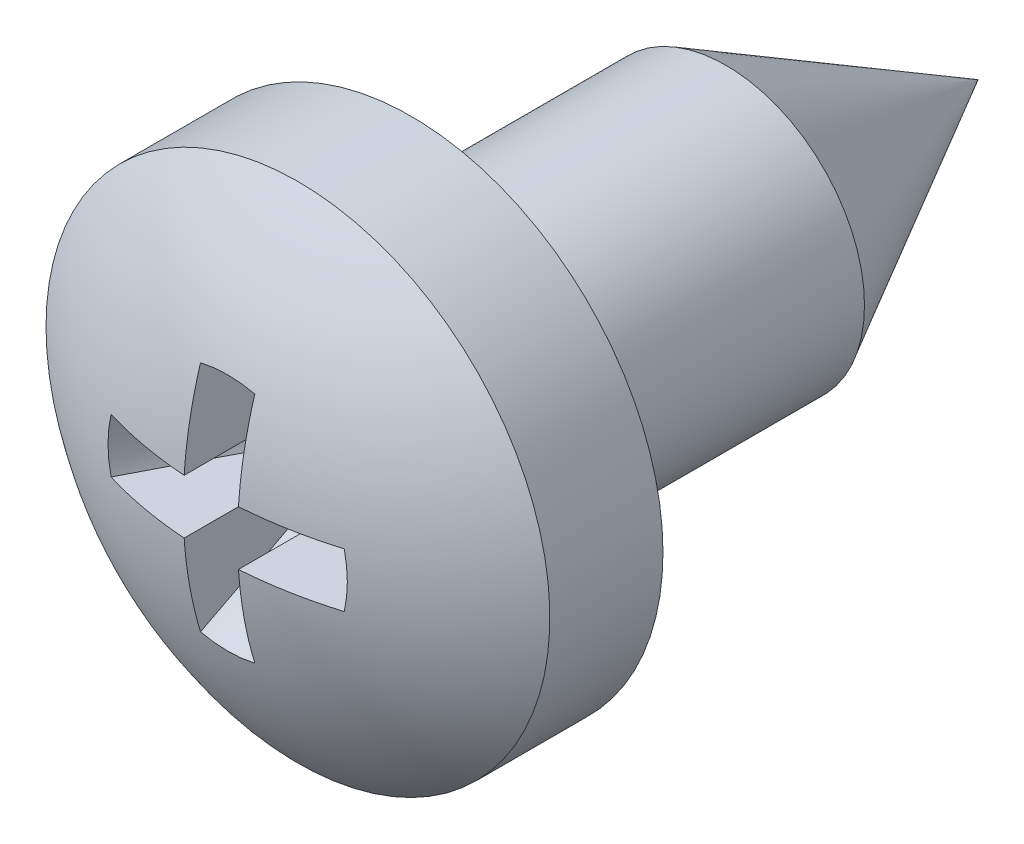
SolidWorks part; units mm, degrees
material "Alloy Steel"
ref_plane "Спереди" through (0, 0, 0) normal (0, 0, 1) x (1, 0, 0)
ref_plane "Сверху" through (0, 0, 0) normal (0, 1, 0) x (1, 0, 0)
ref_plane "Справа" through (0, 0, 0) normal (1, 0, 0) x (0, 0, -1)
sketch "Sketch1" plane through (0, 0, 0) normal (1, 0, 0) x (0, 0, -1)
  line L0 (104.6162, 0) -> (-104.6162, 0) construction
  line L1 (0, -65.8131) -> (0, 65.8131) construction
  line L3 (0.702, 2) -> (1.6, 2)
  line L4 (1.6, 2) -> (1.6, 1.1)
  line L5 (1.6, 1.1) -> (6.1, 1.1)
  line L6 (6.1, 1.1) -> (6.1, 0)
  line L7 (6.1, 0) -> (0, 0)
  arc A0 (0.702, 2) -> (0, 0) centre (3.2, 0) ccw
  point P4 (0, 0)
  point P8 (0, 0)
  dimension "D1" = 3.2
  dimension "D4" = 4
  dimension "D5" = 2.2
  dimension "D2" = 1.6
  dimension "D3" = 4.5
revolve "BaseBody" add sketch "Sketch1" angle 360 about L0
cosmetic thread "Cosmetic Thread1" parameters "D1"=3.7, "D2"=1.63
cosmetic thread "Cosmetic Thread2" [suppressed] parameters "D1"=3.7, "D2"=1.63
cosmetic thread "Cosmetic Thread3" [suppressed] parameters "D1"=3.7, "D2"=1.63
sketch "Sketch2" plane through (0, 0, 0) normal (0, 0, 1) x (1, 0, 0)
  line L0 (2.967, 0) -> (-2.967, 0) construction
  line L1 (0, -2.1958) -> (0, 2.1958) construction
  line L2 (-0.2157, 0.9252) -> (-0.2157, 0)
  line L3 (-0.2157, 0) -> (0.2157, 0)
  line L4 (0.2157, 0) -> (0.2157, 0.9252)
  line L5 (0.2157, 0) -> (-0.2157, 0.4313) construction
  arc A0 (0.2157, 0.9252) -> (-0.2157, 0.9252) centre (0, 0) ccw
  point P4 (0, 0)
  point P8 (0, 0)
  dimension "m" = 1.9
  dimension "D2" = 45
  dimension "D3" = 0.61
extrude "Slot" cut sketch "Sketch2" against normal blind 1.9
pattern_circular "CirPattern1" count 4 over 360 about axis through (0, 0, 0) along (0, 0, 1) of "Slot"
sketch "Sketch3" [suppressed] plane through (0, 0, 0) normal (0, 0, 1) x (1, 0, 0)
  line L0 (2.5828, 0) -> (-2.5828, 0) construction
  line L1 (0, -2.1055) -> (0, 2.1055) construction
  line L2 (0, 0) -> (-1.0643, 1.0643) construction
  line L3 (-0.7071, 0.7071) -> (-0.4001, 0.2687)
  line L4 (-0.4001, 0.2687) -> (-0.2687, 0.2687)
  line L5 (-0.2687, 0.2687) -> (-0.2687, 0.4001)
  line L6 (-0.2687, 0.4001) -> (-0.7071, 0.7071)
  line L7 (0.2687, 0) -> (0.2687, 0.9632) construction
  line L8 (-0.2687, 0.9632) -> (-0.2687, 0) construction
  line L9 (0.2687, 0) -> (-0.2687, 0.5374) construction
  circle A0 centre (0, 0) radius 1 construction
  point P4 (0, 0)
  point P8 (0, 0)
  dimension "D4" = 1.9
  dimension "D1" = 45
  dimension "D2" = 10
  dimension "D3" = 10
  dimension "u" = 0.95
  dimension "D5" = 0.61
  dimension "D6" = 45
extrude "Slot2" [suppressed] cut sketch "Sketch3" against normal blind 1.9
pattern_circular "CirPattern2" [suppressed] count 4 over 360
sketch "Sketch4" plane through (0, 0, 0) normal (1, 0, 0) x (0, 0, -1)
  line L0 (5.0682, 0) -> (-5.0682, 0) construction
  line L1 (0.6251, 1.9) -> (1.6, 1.9)
  line L2 (0, -2.7234) -> (0, 2.7234) construction
  line L5 (1.6, 1.9) -> (1.6, 1.1)
  line L6 (1.6, 1.1) -> (1.91, 1.1)
  line L7 (1.91, 1.1) -> (1.91, 0)
  line L8 (1.91, 0) -> (1.4527, 0)
  line L10 (1.4527, 0) -> (1.2374, 0.405)
  line L11 (1.2374, 0.405) -> (0.1443, 0.95)
  arc A0 (0.6251, 1.9) -> (0.1443, 0.95) centre (3.2, 0) ccw
  point P3 (0, 0)
  point P7 (0, 0)
  dimension "D4" = 1.9
  dimension "D3" = 3.2
  dimension "D1" = 28
  dimension "D2" = 26.5
  dimension "D5" = 0.81
  dimension "D6" = 2.2
  dimension "D7" = 1.91
  dimension "D9" = 1.6
  dimension "D8" = 3.8
revolve "BaseBodySlot" add sketch "Sketch4" angle 360 about L0
chamfer "Chamfer1" distance 2 distance2 1.099 1 edges at (-1.1, 0, -6.1)
chamfer "Chamfer2" [suppressed] distance 1.6 distance2 0.365
chamfer "Chamfer3" [suppressed] distance 1.6 angle 57.296
fillet "Fillet" [suppressed] radius 0.5
fillet "Fillet1" radius 0.1 1 edges at (-1.1, 0, -1.6)
equation "\"D1@Slot\" = \"m@Sketch2\""
equation "\"D4@Sketch3\" = \"m@Sketch2\""
equation "\"D5@Sketch3\"=\"D3@Sketch2\""
equation "\"D1@Slot2\" = \"m@Sketch2\""
equation "\"D4@Sketch4\"=\"m@Sketch2\""
equation "\"D6@Sketch4\"=\"D5@Sketch1\""
equation "\"D3@Chamfer2\"=\"D3@Chamfer1\""
equation "\"D3@Chamfer3\"=\"D3@Chamfer1\""
equation "\"D1@Chamfer2\"=\"D1@Chamfer1\""
equation "\"D1@Chamfer3\"=\"D1@Chamfer1\""
equation "\"D7@Sketch4\"=\"m@Sketch2\"+0.01"
equation "\"D8@Sketch4\"=\"D4@Sketch1\"-0.2"
equation "\"D3@Sketch4\"=\"D1@Sketch1\""
equation "\"D9@Sketch4\"=\"D2@Sketch1\""
